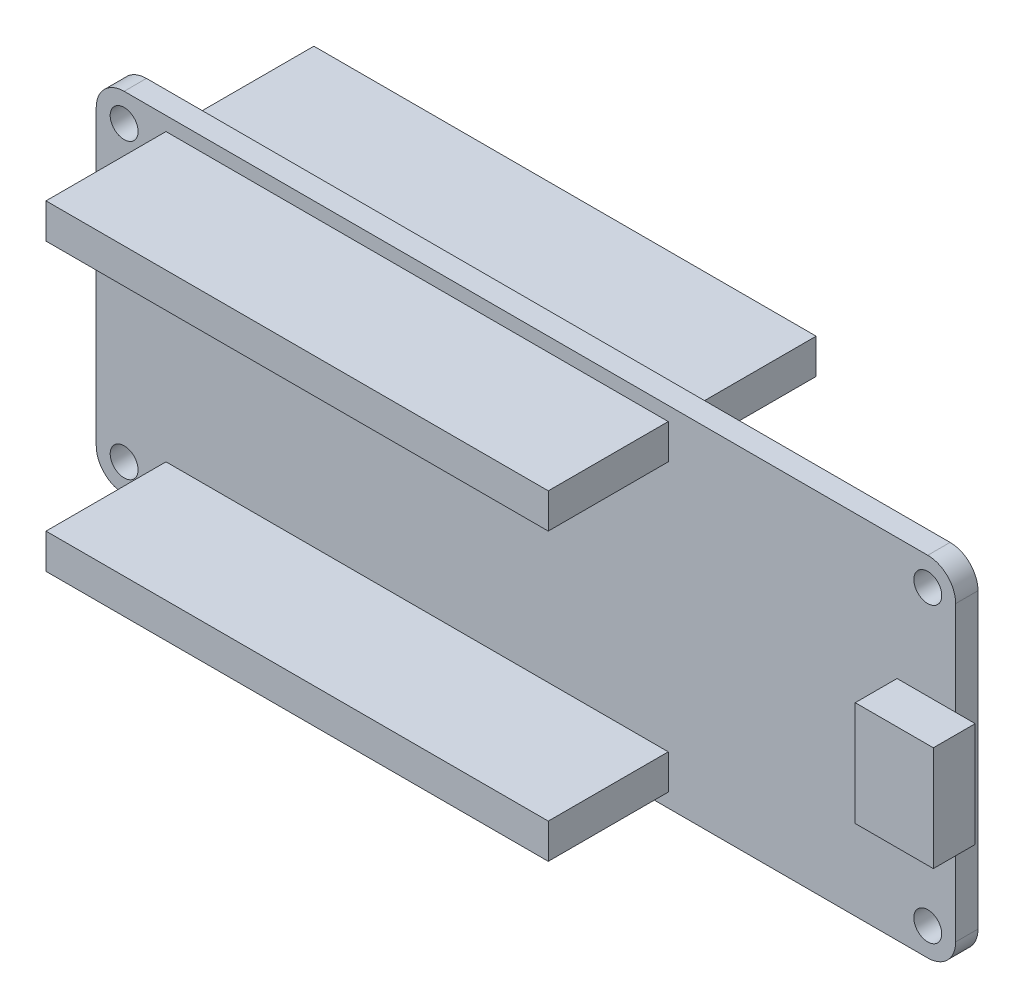
SolidWorks part; units mm, degrees
ref_plane "Piano frontale" through (0, 0, 0) normal (0, 0, 1) x (1, 0, 0)
ref_plane "Piano superiore" through (0, 0, 0) normal (0, 1, 0) x (1, 0, 0)
ref_plane "Piano destro" through (0, 0, 0) normal (1, 0, 0) x (0, 0, -1)
sketch "Schizzo1" plane through (0, 0, 0) normal (0, 0, 1) x (1, 0, 0)
  line L1 (-30.8, -12.5) -> (30.8, -12.5)
  line L2 (-30.8, -12.5) -> (-30.8, 12.5)
  line L3 (-30.8, 12.5) -> (30.8, 12.5)
  line L4 (30.8, -12.5) -> (30.8, 12.5)
  dimension "D1" = 25
  dimension "D2" = 61.6
  dimension "D3" = 30.8
  dimension "D4" = 12.5
extrude "Estrusione-Estrusione1" add sketch "Schizzo1" along normal blind 1.6
sketch "Schizzo2" plane through (0, 0, 1.6) normal (0, 0, 1) x (1, 0, 0)
  line L0 (30.8, 12.5) -> (-30.8, 12.5) construction
  line L1 (-30.8, 12.5) -> (-30.8, -12.5) construction
  line L2 (30.8, -12.5) -> (30.8, 12.5) construction
  line L3 (-30.8, -12.5) -> (30.8, -12.5) construction
  circle A0 centre (-28.8, 10.5) radius 1
  circle A1 centre (28.8, 10.5) radius 1
  circle A2 centre (28.8, -10.5) radius 1
  circle A3 centre (-28.8, -10.5) radius 1
  dimension "D1" = 2
  dimension "D2" = 2
  dimension "D3" = 2
  dimension "D4" = 2
  dimension "D6" = 2
  dimension "D7" = 2
  dimension "D9" = 2
  dimension "D10" = 2
  dimension "D12" = 2
  dimension "D5" = 2
  dimension "D8" = 2
  dimension "D11" = 2
extrude "Taglio-Estrusione1" cut sketch "Schizzo2" against normal blind 1.6
fillet "Raccordo1" radius 2 4 edges at (30.8, -12.5, 0.8) (30.8, 12.5, 0.8) (-30.8, -12.5, 0.8) (-30.8, 12.5, 0.8)
sketch "Schizzo3" plane through (0, 0, 1.6) normal (0, 0, 1) x (1, 0, 0)
  line L0 (30.8, -10.5) -> (30.8, 10.5) construction
  line L1 (26.6, -3.75) -> (32.2, -3.75)
  line L2 (26.6, -3.75) -> (26.6, 3.75)
  line L3 (26.6, 3.75) -> (32.2, 3.75)
  line L4 (32.2, -3.75) -> (32.2, 3.75)
  line L5 (28.8, 12.5) -> (-28.8, 12.5) construction
  dimension "D1" = 7.5
  dimension "D2" = 5.6
  dimension "D3" = 1.4
  dimension "D4" = 8.75
extrude "Estrusione-Estrusione2" add sketch "Schizzo3" along normal blind 3
sketch "Schizzo4" plane through (0, 0, 1.6) normal (0, 0, 1) x (1, 0, 0)
  line L0 (-30.8, 10.5) -> (-30.8, -10.5) construction
  line L1 (-25.8, 11.5) -> (10.2, 11.5)
  line L2 (-25.8, 11.5) -> (-25.8, 9)
  line L3 (-25.8, 9) -> (10.2, 9)
  line L4 (10.2, 11.5) -> (10.2, 9)
  line L5 (-25.8, -9) -> (10.2, -9)
  line L6 (-25.8, -9) -> (-25.8, -11.5)
  line L7 (-25.8, -11.5) -> (10.2, -11.5)
  line L8 (10.2, -9) -> (10.2, -11.5)
  line L9 (28.8, 12.5) -> (-28.8, 12.5) construction
  line L10 (-28.8, -12.5) -> (28.8, -12.5) construction
  dimension "D1" = 5
  dimension "D2" = 36
  dimension "D3" = 36
  dimension "D4" = 5
  dimension "D5" = 2.5
  dimension "D6" = 2.5
  dimension "D7" = 1
  dimension "D8" = 1
extrude "Estrusione-Estrusione3" add sketch "Schizzo4" along normal blind 8.6 and the other way blind 10.6
